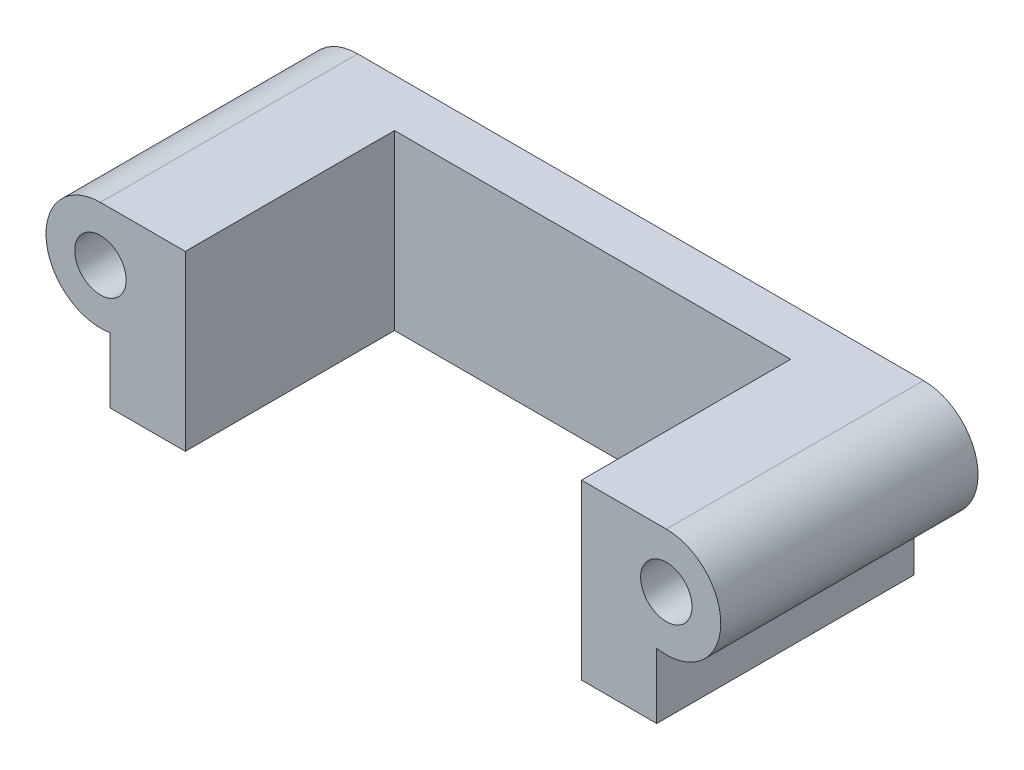
SolidWorks part; units mm, degrees
ref_plane "Plano frontal" through (0, 0, 0) normal (0, 0, 1) x (1, 0, 0)
ref_plane "Plano superior" through (0, 0, 0) normal (0, 1, 0) x (1, 0, 0)
ref_plane "Plano direito" through (0, 0, 0) normal (1, 0, 0) x (0, 0, -1)
sketch "Esboço1" plane through (0, 0, 0) normal (0, 0, 1) x (1, 0, 0)
  line L0 (0, 3.175) -> (33, 3.175)
  line L1 (16.5, 3.175) -> (16.5, -6.925) construction
  line L2 (0.5612, -6.925) -> (32.4388, -6.925)
  line L3 (0.5612, -6.925) -> (0.5612, -3.125)
  line L4 (32.4388, -6.925) -> (32.4388, -3.125)
  circle A0 centre (0, 0) radius 1.5
  circle A1 centre (33, 0) radius 1.5
  arc A2 (0, 3.175) -> (0.5612, -3.125) centre (0, 0) ccw
  arc A3 (32.4388, -3.125) -> (33, 3.175) centre (33, 0) ccw
  point P5 (1.5, 0)
  point P6 (31.5, 0)
  dimension "D1" = 3
  dimension "D2" = 6.35
  dimension "D3" = 10.1
  dimension "D4" = 3.8
  dimension "D6" = 30
extrude "Ressalto-extrusão1" add sketch "Esboço1" along normal blind 15
sketch "Esboço2" plane through (0, 0, 0) normal (0, 1, 0) x (1, 0, 0)
  line L0 (33, -15) -> (0, -15) construction
  line L1 (4.95, -15) -> (28.05, -15)
  line L2 (4.95, -15) -> (4.95, -2.8)
  line L3 (4.95, -2.8) -> (28.05, -2.8)
  line L4 (28.05, -15) -> (28.05, -2.8)
  line L5 (16.5, 0) -> (16.5, -15) construction
  line L6 (33, 0) -> (0, 0) construction
  dimension "D1" = 2.8
  dimension "D2" = 23.1
extrude "Corte-extrusão1" cut sketch "Esboço2" along normal through all both and the other way through all
